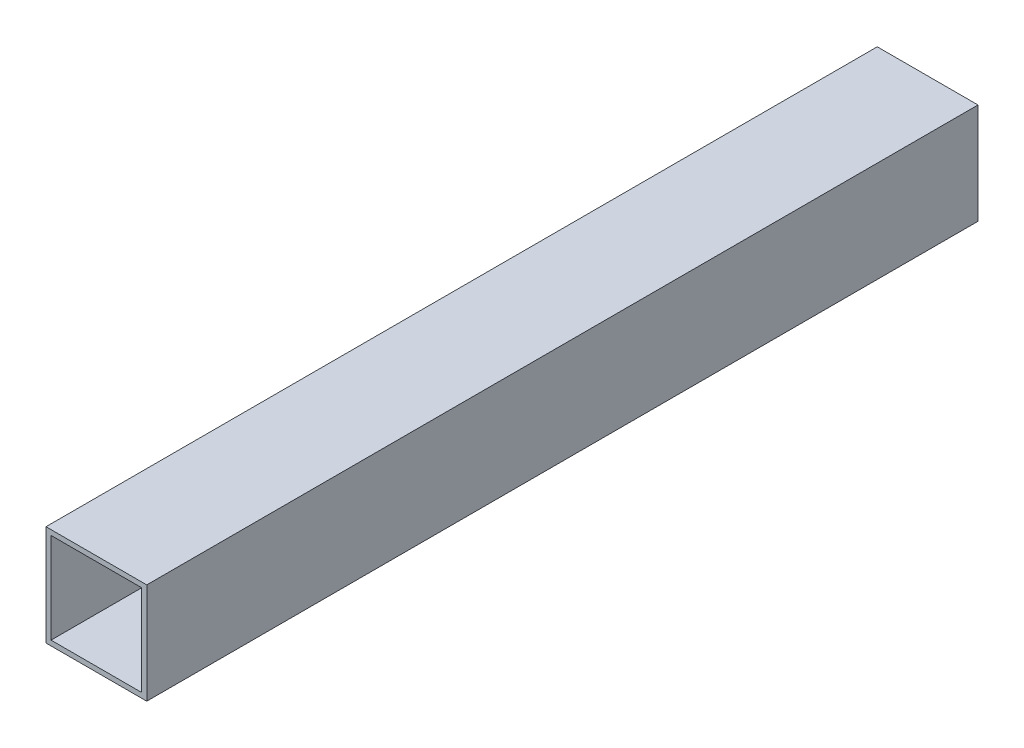
SolidWorks part; units mm, degrees
ref_plane "Alzado" through (0, 0, 0) normal (0, 0, 1) x (1, 0, 0)
ref_plane "Planta" through (0, 0, 0) normal (0, 1, 0) x (1, 0, 0)
ref_plane "Vista lateral" through (0, 0, 0) normal (1, 0, 0) x (0, 0, -1)
sketch "Croquis1" plane through (0, 0, 0) normal (0, 0, 1) x (1, 0, 0)
  line L1 (20, -20) -> (-20, -20)
  line L2 (20, -20) -> (20, 20)
  line L3 (20, 20) -> (-20, 20)
  line L4 (-20, -20) -> (-20, 20)
  line L5 (20, -20) -> (-20, 20) construction
  line L6 (20, 20) -> (-20, -20) construction
  point P0 (0, 0)
  dimension "D1" = 40
  dimension "D2" = 40
extrude "Extruir-Lámina1" add sketch "Croquis1" along normal blind 330 thin
